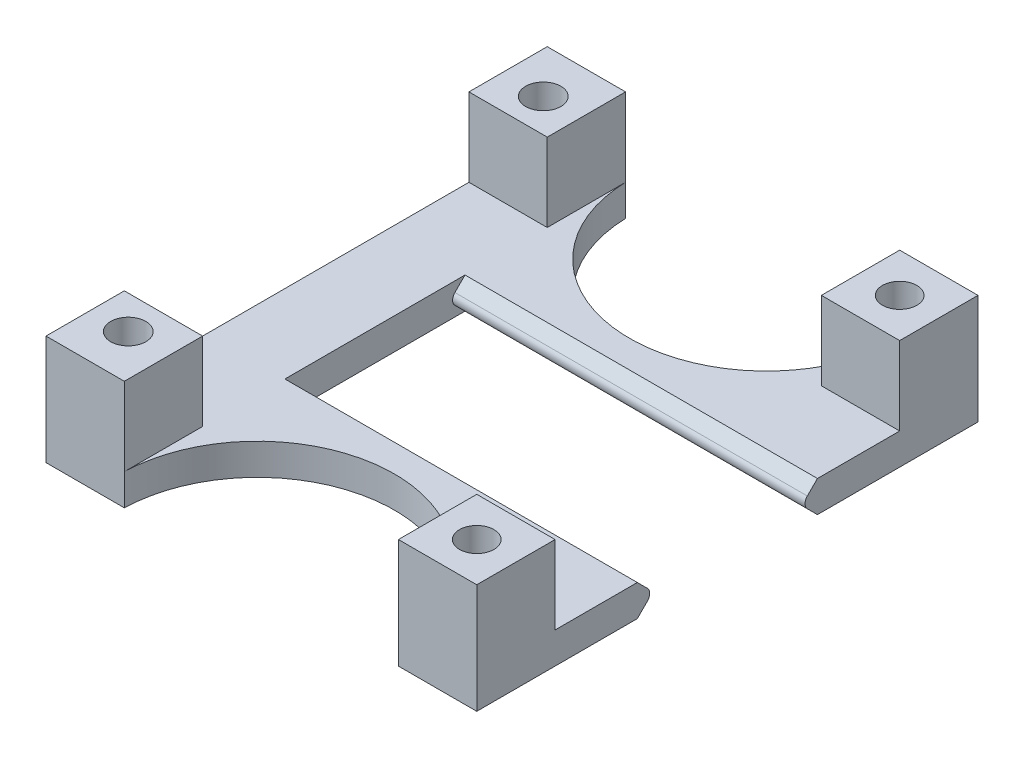
SolidWorks part; units mm, degrees
ref_plane "Front Plane" through (0, 0, 0) normal (0, 0, 1) x (1, 0, 0)
ref_plane "Top Plane" through (0, 0, 0) normal (0, 1, 0) x (1, 0, 0)
ref_plane "Right Plane" through (0, 0, 0) normal (1, 0, 0) x (0, 0, -1)
sketch "Sketch1" plane through (0, 0, 0) normal (0, 1, 0) x (1, 0, 0)
  line L0 (10, 10) -> (10, -10)
  line L2 (0, -20) -> (0, 20)
  line L4 (55, -20) -> (55, 20) construction
  line L5 (10, -10) -> (45, -10)
  line L6 (45, -10) -> (45, 10) construction
  line L7 (45, 10) -> (10, 10)
  line L8 (45, 10) -> (55, 10)
  line L11 (55, 10) -> (55, 20)
  line L13 (27.5, -20) -> (27.5, -10) construction
  line L14 (27.5, 10) -> (27.5, 20) construction
  line L16 (45, -10) -> (55, -10)
  line L17 (55, -20) -> (55, -10)
  line L18 (55, -20) -> (55, -32)
  line L19 (55, -32) -> (45, -32)
  line L21 (55, 20) -> (55, 32)
  line L22 (55, 32) -> (45, 32)
  line L24 (0, -20) -> (0, -32)
  line L27 (0, 20) -> (0, 32)
  line L30 (-7.7, 0) -> (7.7, 0) construction
  line L31 (0, 0) -> (55, 0) construction
  line L32 (10, -32) -> (0, -32)
  line L34 (10, 32) -> (0, 32)
  arc A26 (45, -32) -> (10, -32) centre (27.5, -32.5074) ccw
  arc A27 (45, 32) -> (10, 32) centre (27.5, 32.5074) cw
  circle A46 centre (50, 27) radius 2.2
  circle A47 centre (50, -27) radius 2.2
  circle A49 centre (4.7553, -26.2506) radius 2.2479 construction
  circle A50 centre (4.7553, -26.2506) radius 2.2479
  circle A51 centre (5.2446, 26.2471) radius 2.2479 construction
  circle A52 centre (5.2446, 26.2471) radius 2.2479
  point P30 (27.5, -15)
  point P35 (27.5, 15)
  point P36 (27.5, -10)
  point P39 (0, 0)
  dimension "D18" = 4.4
  dimension "D1" = 40
  dimension "D2" = 55
  dimension "D24" = 10
  dimension "D13" = 5
  dimension "D16" = 5
  dimension "D7" = 10
  dimension "D9" = 5
  dimension "D14" = 5
  dimension "D4" = 20
  dimension "D5" = 10
  dimension "D3" = 10
  dimension "D6" = 35
  dimension "D8" = 12
  dimension "D10" = 10
extrude "Extrude-Body" add sketch "Sketch1" along normal blind 4
sketch "Sketch5" plane through (0, 4, 0) normal (0, 1, 0) x (1, 0, 0)
  line L6 (10, -32) -> (0, -32) construction
  line L9 (45, -22) -> (55, -22)
  line L21 (55, -22) -> (55, -32)
  line L23 (0, -32) -> (0, 32) construction
  line L34 (10, 32) -> (0, 32) construction
  line L36 (55, -32) -> (45, -32)
  line L37 (45, -32) -> (45, -22)
  line L38 (55, 22) -> (55, 32)
  line L39 (55, 32) -> (45, 32)
  line L41 (45, 32) -> (45, 22)
  line L42 (45, 22) -> (55, 22)
  line L43 (10, 22) -> (10, 32)
  line L44 (10, 32) -> (0, 32)
  line L46 (0, 32) -> (0, 22)
  line L47 (0, -32) -> (0, 32) construction
  line L48 (0, 22) -> (10, 22)
  line L49 (10, -22) -> (0, -22)
  line L50 (0, -22) -> (0, -32)
  line L51 (0, -32) -> (10, -32)
  line L52 (10, -32) -> (10, -22)
  circle A0 centre (50, 27) radius 2.2
  circle A3 centre (50, -27) radius 2.2
  circle A11 centre (50, 27) radius 2.2 construction
  circle A12 centre (50, -27) radius 2.2 construction
  circle A13 centre (5.2446, 26.2471) radius 2.2479 construction
  circle A14 centre (5.2446, 26.2471) radius 2.2479
  circle A15 centre (4.7553, -26.2506) radius 2.2479 construction
  circle A16 centre (4.7553, -26.2506) radius 2.2479
  dimension "D1" = 10
  dimension "D2" = 10
  dimension "D3" = 10
  dimension "D4" = 10
  dimension "D5" = 10
  dimension "D6" = 10
  dimension "D8" = 10
extrude "Extrude-Legs" add sketch "Sketch5" along normal blind 10
sketch "Sketch6" plane through (0, 4, 0) normal (0, 1, 0) x (1, 0, 0)
  line L0 (55, -10) -> (55, -22) construction
  line L1 (10, -10) -> (55, -10)
  line L2 (10, -10) -> (10, -9.5)
  line L3 (10, -9.5) -> (55, -9.5)
  line L4 (55, -10) -> (55, -9.5)
  line L5 (10, 10) -> (55, 10)
  line L6 (10, 10) -> (10, 9.5)
  line L7 (10, 9.5) -> (55, 9.5)
  line L8 (55, 10) -> (55, 9.5)
  line L9 (55, 10) -> (55, 22) construction
  dimension "D1" = 19
extrude "Boss-Extrude1" add sketch "Sketch6" against normal up to surface (4 mm away) up to face at (5.2446, 0, -23.9992)
sketch "Sketch7" plane through (55, 0, 0) normal (1, 0, 0) x (0, 0, -1)
  line L0 (-10.2071, 2.7071) -> (-11.5, 4)
  line L1 (-9.5, 0) -> (-9.5, 4) construction
  line L2 (-9.5, 4) -> (-22, 4) construction
  line L3 (-10.2071, 1.2929) -> (-11.5, 0)
  line L4 (-9.5, 0) -> (-32, 0) construction
  line L5 (10.2071, 2.7071) -> (11.5, 4)
  line L6 (9.5, 0) -> (9.5, 4) construction
  line L7 (9.5, 4) -> (22, 4) construction
  line L8 (10.2071, 1.2929) -> (11.5, 0)
  line L9 (9.5, 0) -> (32, 0) construction
  line L10 (11.5, 4) -> (9.5, 4)
  line L11 (9.5, 0) -> (9.5, 4) construction
  line L12 (9.5, 4) -> (9.5, 0)
  line L13 (9.5, 0) -> (11.5, 0)
  line L14 (-11.5, 4) -> (-9.5, 4)
  line L15 (-9.5, 4) -> (-9.5, 0)
  line L16 (-9.5, 0) -> (-11.5, 0)
  line L17 (0, 0) -> (0, 8.2974) construction
  arc A0 (10.2071, 2.7071) -> (10.2071, 1.2929) centre (10.9142, 2) ccw
  arc A1 (-10.2071, 2.7071) -> (-10.2071, 1.2929) centre (-10.9142, 2) cw
  point P36 (9.5, 2)
  point P39 (-9.5, 2)
  dimension "D3" = 1
  dimension "D1" = 45
  dimension "D2" = 45
extrude "Cut-Extrude1" cut sketch "Sketch7" against normal up to surface (45 mm away) up to face at (10, 2, 0)
equation "\"boltdiameter\"=4.4"
equation "\"D18@Sketch1\"=\"boltdiameter\""
equation "\"boltfacediameter\"=7"
equation "\"insetNutFlat\"=8.4"
equation "\"screwInset\"=8.43"
equation "\"slotLength\"=80"
